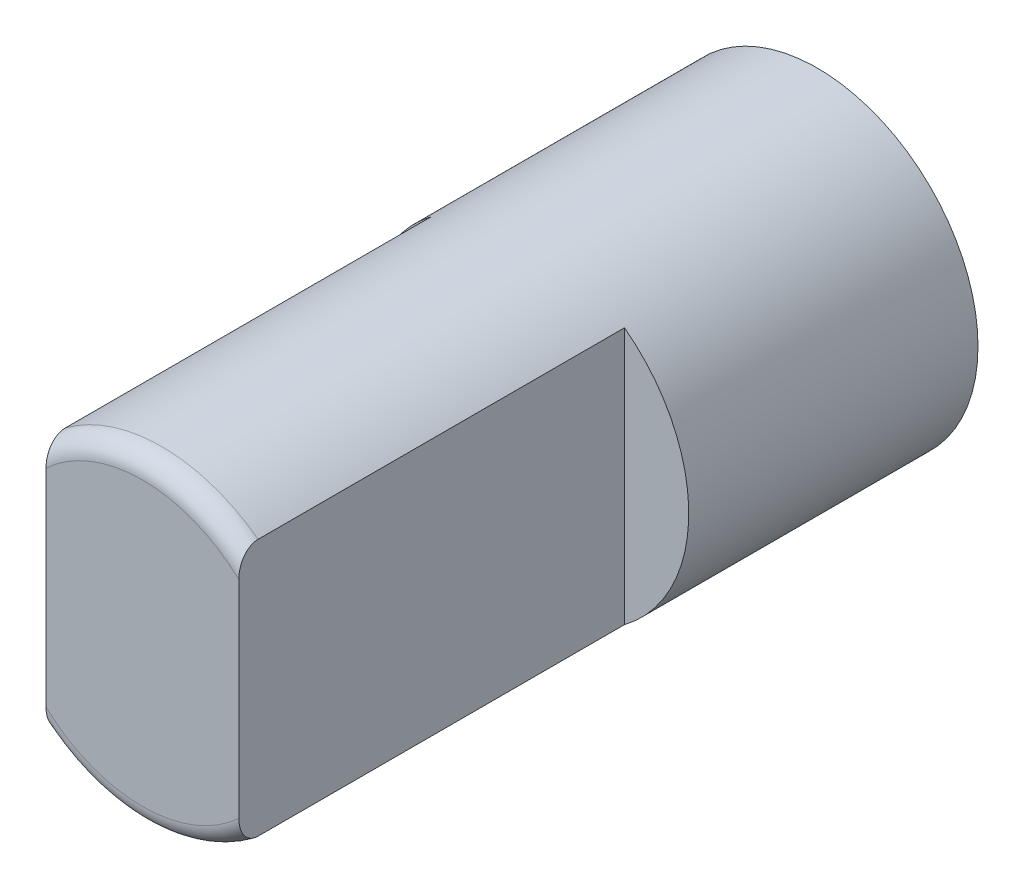
SolidWorks part; units mm, degrees
ref_plane "Plan de face" through (0, 0, 0) normal (0, 0, 1) x (1, 0, 0)
ref_plane "Plan de dessus" through (0, 0, 0) normal (0, 1, 0) x (1, 0, 0)
ref_plane "Plan de droite" through (0, 0, 0) normal (1, 0, 0) x (0, 0, -1)
sketch "Esquisse1" plane through (0, 0, 0) normal (0, 0, 1) x (1, 0, 0)
  circle A0 centre (0, 0) radius 2.5
  point P2 (0, 0)
  dimension "D1" = 5
extrude "Boss.-Extru.1" add sketch "Esquisse1" along normal blind 10.5
sketch "Esquisse3" plane through (0, 0, 10.5) normal (0, 0, 1) x (1, 0, 0)
  line L0 (0, 2.5) -> (0, -2.7613) construction
  line L2 (1.5, 2) -> (1.5, -2)
  line L4 (-1.5, -2) -> (-1.5, 2)
  circle A0 centre (0, 0) radius 2.5 construction
  arc A1 (-1.5, 2) -> (-1.5, -2) centre (0, 0) ccw
  arc A2 (1.5, -2) -> (1.5, 2) centre (0, 0) ccw
  point P9 (0, 2.5)
  dimension "D1" = 5
  dimension "D2" = 3
extrude "Enlèv. mat.-Extru.2" cut sketch "Esquisse3" against normal blind 6
fillet "Congé1" radius 0.3 2 edges at (0, 2.5, 10.5) (0, -2.5, 10.5)
